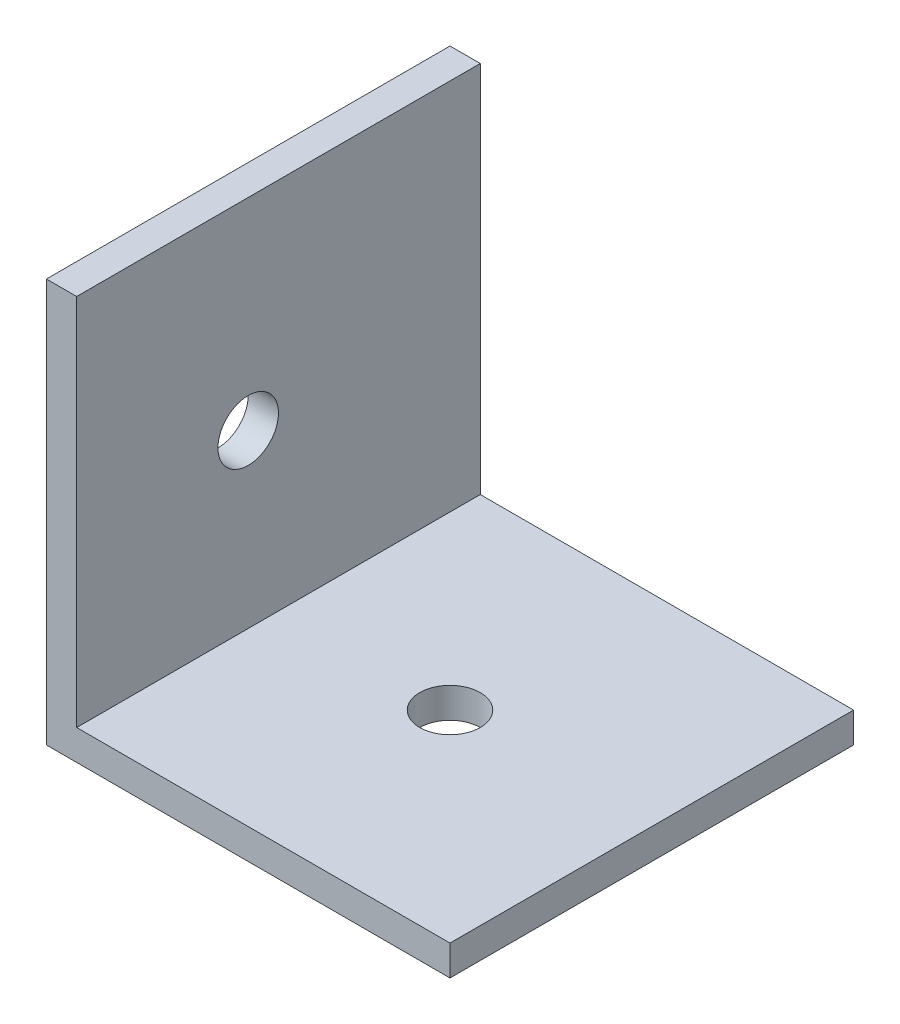
SolidWorks part; units mm, degrees
ref_plane "Plan de face" through (0, 0, 0) normal (0, 0, 1) x (1, 0, 0)
ref_plane "Plan de dessus" through (0, 0, 0) normal (0, 1, 0) x (1, 0, 0)
ref_plane "Plan de droite" through (0, 0, 0) normal (1, 0, 0) x (0, 0, -1)
sketch "Esquisse1" plane through (0, 0, 0) normal (0, 0, 1) x (1, 0, 0)
  line L0 (0, 0) -> (20, 0)
  line L1 (20, 0) -> (20, 1.5)
  line L2 (20, 1.5) -> (1.5, 1.5)
  line L3 (1.5, 1.5) -> (1.5, 20)
  line L4 (1.5, 20) -> (0, 20)
  line L5 (0, 20) -> (0, 0)
  dimension "D1" = 1.5
  dimension "D2" = 1.5
  dimension "D3" = 20
  dimension "D4" = 20
extrude "Extrusion1" add sketch "Esquisse1" along normal blind 20
sketch "Esquisse7" plane through (0, 1.5, 0) normal (0, 1, 0) x (-1, 0, 0)
  line L0 (-20, 20) -> (-20, 0) construction
  line L1 (-20, 20) -> (-1.5, 20) construction
  circle A0 centre (-10, 10) radius 1.5
  dimension "D2" = 10
  dimension "D3" = 10
extrude "Extrusion7" cut sketch "Esquisse7" against normal through all
sketch "Esquisse9" plane through (1.5, 0, 0) normal (1, 0, 0) x (0, 0, -1)
  line L0 (-20, 1.5) -> (-20, 20) construction
  line L1 (-20, 20) -> (0, 20) construction
  circle A0 centre (-11.5, 10) radius 1.5
  dimension "D1" = 8.5
  dimension "D3" = 10
extrude "Extrusion8" cut sketch "Esquisse9" against normal through all
